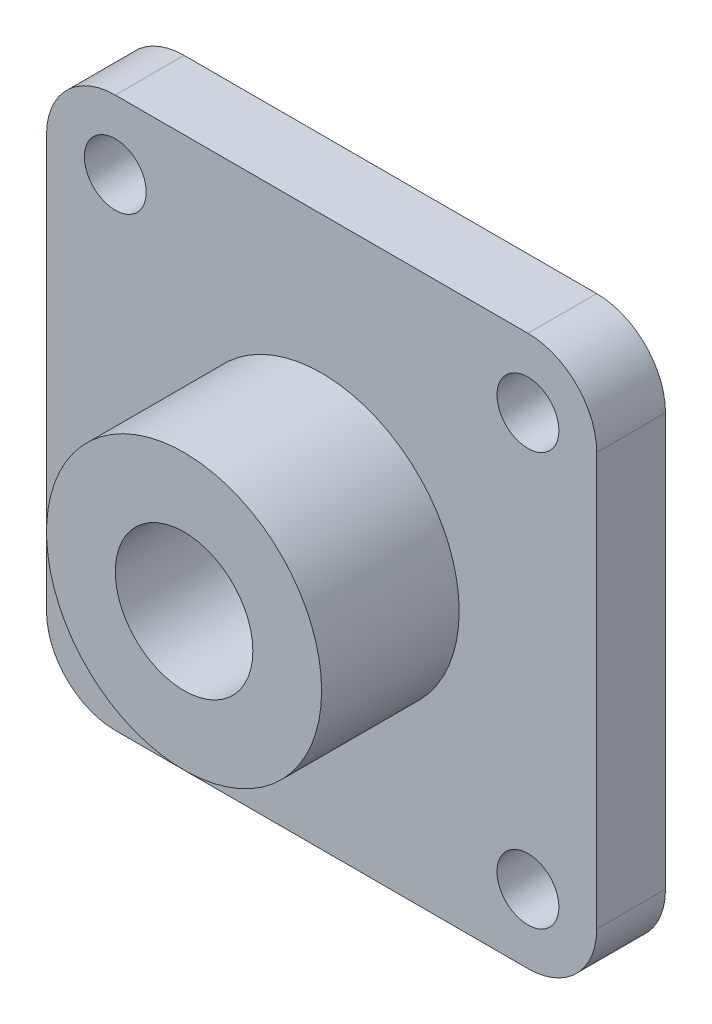
SolidWorks part; units mm, degrees
ref_plane "前视基准面" through (0, 0, 0) normal (0, 0, 1) x (1, 0, 0)
ref_plane "上视基准面" through (0, 0, 0) normal (0, 1, 0) x (1, 0, 0)
ref_plane "右视基准面" through (0, 0, 0) normal (1, 0, 0) x (0, 0, -1)
sketch "草图1" plane through (0, 0, 0) normal (0, 0, 1) x (1, 0, 0)
  line L0 (-30, -40) -> (30, -40)
  line L1 (40, -30) -> (40, 30)
  line L2 (30, 40) -> (-30, 40)
  line L3 (-40, 30) -> (-40, -30)
  arc A0 (-40, -30) -> (-30, -40) centre (-30, -30) ccw
  arc A1 (30, -40) -> (40, -30) centre (30, -30) ccw
  arc A2 (40, 30) -> (30, 40) centre (30, 30) ccw
  arc A3 (-30, 40) -> (-40, 30) centre (-30, 30) ccw
extrude "凸台-拉伸1" add sketch "草图1" along normal blind 10
ref_plane "基准面1" through (0, 0, 10) normal (0, 0, 1) x (1, 0, 0)
sketch "草图2" plane through (0, 0, 10) normal (0, 0, 1) x (1, 0, 0)
  circle A0 centre (0, 0) radius 20
extrude "凸台-拉伸2" add sketch "草图2" along normal blind 20
sketch "草图3" plane through (0, 0, 0) normal (0, 0, 1) x (1, 0, 0)
  circle A0 centre (30, 30) radius 4.5
  circle A1 centre (-30, 30) radius 4.5
  circle A2 centre (-30, -30) radius 4.5
  circle A3 centre (30, -30) radius 4.5
extrude "切除-拉伸1" cut sketch "草图3" against normal mid plane 162
ref_plane "基准面2" through (0, 0, 30) normal (0, 0, 1) x (1, 0, 0)
sketch "草图4" plane through (0, 0, 30) normal (0, 0, 1) x (1, 0, 0)
  circle A0 centre (0, 0) radius 10
extrude "切除-拉伸2" cut sketch "草图4" against normal through all
